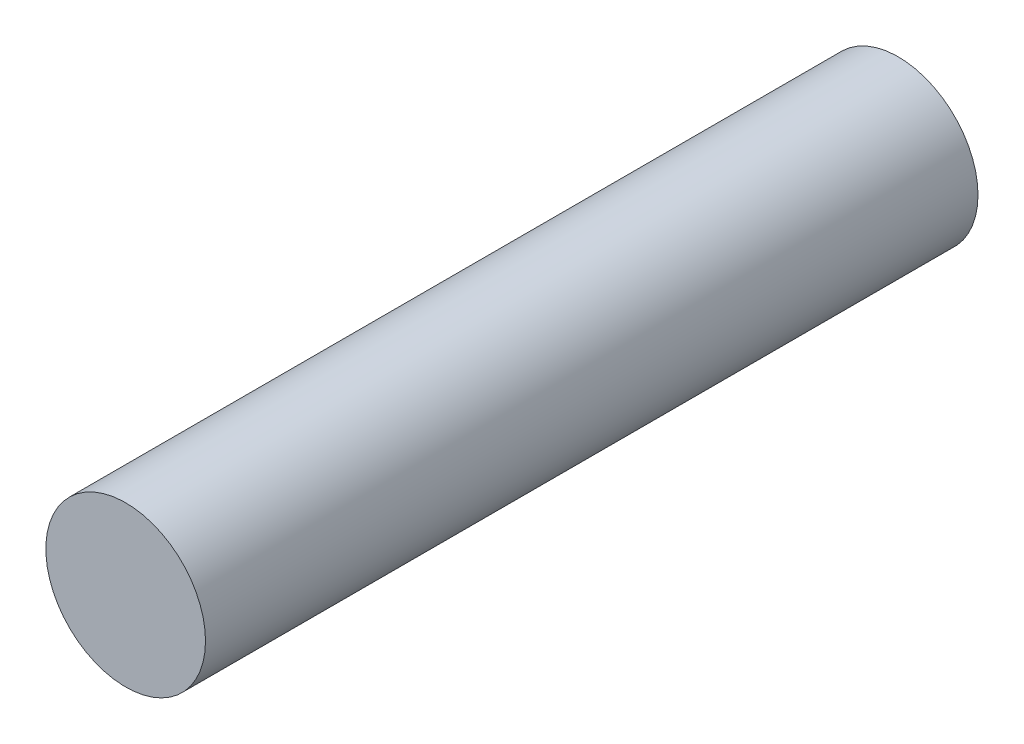
SolidWorks part; units mm, degrees
material "Gray Cast Iron"
ref_plane "Front Plane" through (0, 0, 0) normal (0, 0, 1) x (1, 0, 0)
ref_plane "Top Plane" through (0, 0, 0) normal (0, 1, 0) x (1, 0, 0)
ref_plane "Right Plane" through (0, 0, 0) normal (1, 0, 0) x (0, 0, -1)
sketch "Sketch1" plane through (0, 0, 0) normal (0, 0, 1) x (1, 0, 0)
  line L0 (0, 0) -> (-61584.9867, 0) construction
  line L1 (0, 0) -> (0, 61584.9867) construction
  circle A0 centre (0, 0) radius 31
  dimension "D1" = 62
extrude "Boss-Extrude1" add sketch "Sketch1" along normal mid plane 300
